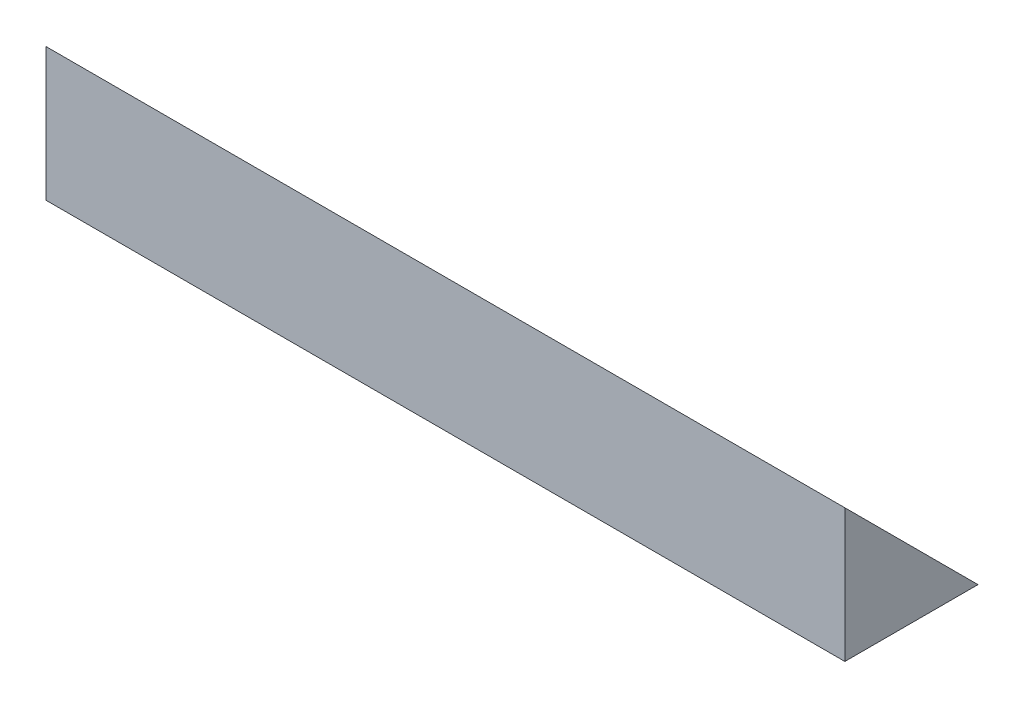
SolidWorks part; units mm, degrees
ref_plane "前视基准面" through (0, 0, 0) normal (0, 0, 1) x (1, 0, 0)
ref_plane "上视基准面" through (0, 0, 0) normal (0, 1, 0) x (1, 0, 0)
ref_plane "右视基准面" through (0, 0, 0) normal (1, 0, 0) x (0, 0, -1)
sketch "草图1" plane through (0, 0, 0) normal (1, 0, 0) x (0, 0, -1)
  line L0 (0, 0) -> (0, -200)
  line L1 (0, -200) -> (200, -200)
  line L2 (200, -200) -> (0, 0)
  dimension "D1" = 200
  dimension "D2" = 200
extrude "凸台-拉伸1" add sketch "草图1" along normal blind 1200
sketch "草图2" plane through (0, 0, 0) normal (0, 0, 1) x (1, 0, 0)
  line L0 (1200, -200) -> (0, -200) construction
  line L1 (1200, -200) -> (0, -200) construction
  line L2 (600, -200) -> (600, -400) construction
  line L3 (1000, -200) -> (1000, -400) construction
  line L4 (200, -200) -> (200, -400) construction
  dimension "D1" = 200
  dimension "D2" = 2
  dimension "D4" = 400
  dimension "D5" = 400
  dimension "D3" = 2
